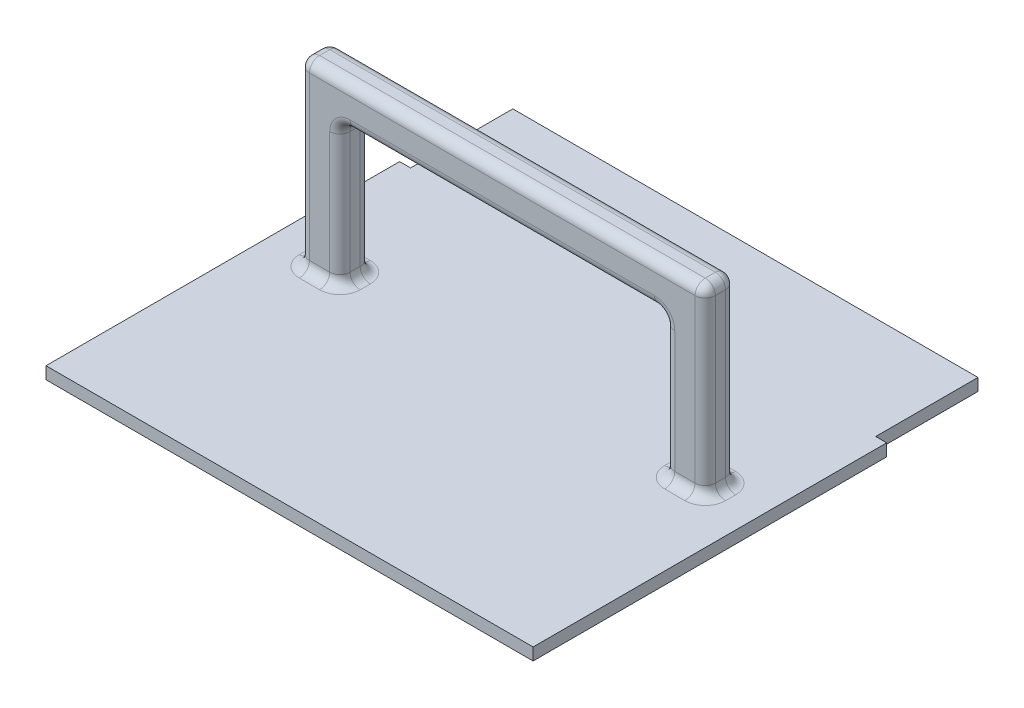
SolidWorks part; units mm, degrees
ref_plane "Front Plane" through (0, 0, 0) normal (0, 0, 1) x (1, 0, 0)
ref_plane "Top Plane" through (0, 0, 0) normal (0, 1, 0) x (1, 0, 0)
ref_plane "Right Plane" through (0, 0, 0) normal (1, 0, 0) x (0, 0, -1)
sketch "Sketch1" plane through (0, 0, 0) normal (0, 1, 0) x (1, 0, 0)
  line L1 (0, 0) -> (152.4, 0)
  line L2 (0, 0) -> (0, 142.621)
  line L3 (0, 142.621) -> (152.4, 142.621)
  line L4 (152.4, 0) -> (152.4, 142.621)
  dimension "D1" = 142.621
  dimension "D2" = 152.4
extrude "Boss-Extrude1" add sketch "Sketch1" along normal blind 3.81
sketch "Sketch2" plane through (0, 3.81, 0) normal (0, 1, 0) x (1, 0, 0)
  line L0 (0, 142.621) -> (0, 0) construction
  line L1 (12.7, 66.548) -> (139.7, 66.548)
  line L2 (12.7, 66.548) -> (12.7, 76.073)
  line L3 (12.7, 76.073) -> (139.7, 76.073)
  line L4 (139.7, 66.548) -> (139.7, 76.073)
  line L5 (0, 0) -> (152.4, 0) construction
  point P6 (139.7, 71.3105)
  dimension "D1" = 127
  dimension "D2" = 9.525
  dimension "D3" = 12.7
  dimension "D4" = 71.3105
extrude "Boss-Extrude2" add sketch "Sketch2" along normal blind 57.15
sketch "Sketch3" plane through (0, 0, -66.548) normal (0, 0, 1) x (1, 0, 0)
  line L0 (12.7, 3.81) -> (139.7, 3.81) construction
  line L1 (25.4, 3.81) -> (127, 3.81)
  line L2 (25.4, 3.81) -> (25.4, 48.26)
  line L3 (25.4, 48.26) -> (127, 48.26)
  line L4 (127, 3.81) -> (127, 48.26)
  line L5 (12.7, 60.96) -> (12.7, 3.81) construction
  line L6 (139.7, 60.96) -> (139.7, 3.81) construction
  line L7 (12.7, 60.96) -> (139.7, 60.96) construction
  dimension "D1" = 12.7
  dimension "D2" = 12.7
  dimension "D3" = 12.7
extrude "Cut-Extrude1" cut sketch "Sketch3" against normal up to next
fillet "Fillet1" radius 3.175 24 edges at (12.7, 32.385, -76.073) (12.7, 60.96, -71.3105) (12.7, 32.385, -66.548) (139.7, 32.385, -76.073) (139.7, 32.385, -66.548) (139.7, 60.96, -71.3105) (76.2, 60.96, -76.073) (76.2, 60.96, -66.548) (139.7, 3.81, -71.3105) (12.7, 3.81, -71.3105) (133.35, 3.81, -66.548) (133.35, 3.81, -76.073) (19.05, 3.81, -76.073) (19.05, 3.81, -66.548) (127, 26.035, -66.548) (127, 3.81, -71.3105) (127, 26.035, -76.073) (25.4, 3.81, -71.3105) (25.4, 26.035, -66.548) (25.4, 26.035, -76.073) (25.4, 48.26, -71.3105) (76.2, 48.26, -66.548) (127, 48.26, -71.3105) (76.2, 48.26, -76.073)
sketch "Sketch4" plane through (0, 3.81, 0) normal (0, 1, 0) x (1, 0, 0)
  line L1 (0, 142.621) -> (3.429, 142.621)
  line L2 (0, 142.621) -> (0, 110.617)
  line L3 (0, 110.617) -> (3.429, 110.617)
  line L4 (3.429, 142.621) -> (3.429, 110.617)
  line L5 (152.4, 142.621) -> (148.971, 142.621)
  line L6 (152.4, 142.621) -> (152.4, 110.617)
  line L7 (152.4, 110.617) -> (148.971, 110.617)
  line L8 (148.971, 142.621) -> (148.971, 110.617)
  dimension "D1" = 3.429
  dimension "D2" = 32.004
extrude "Cut-Extrude2" cut sketch "Sketch4" against normal through all
